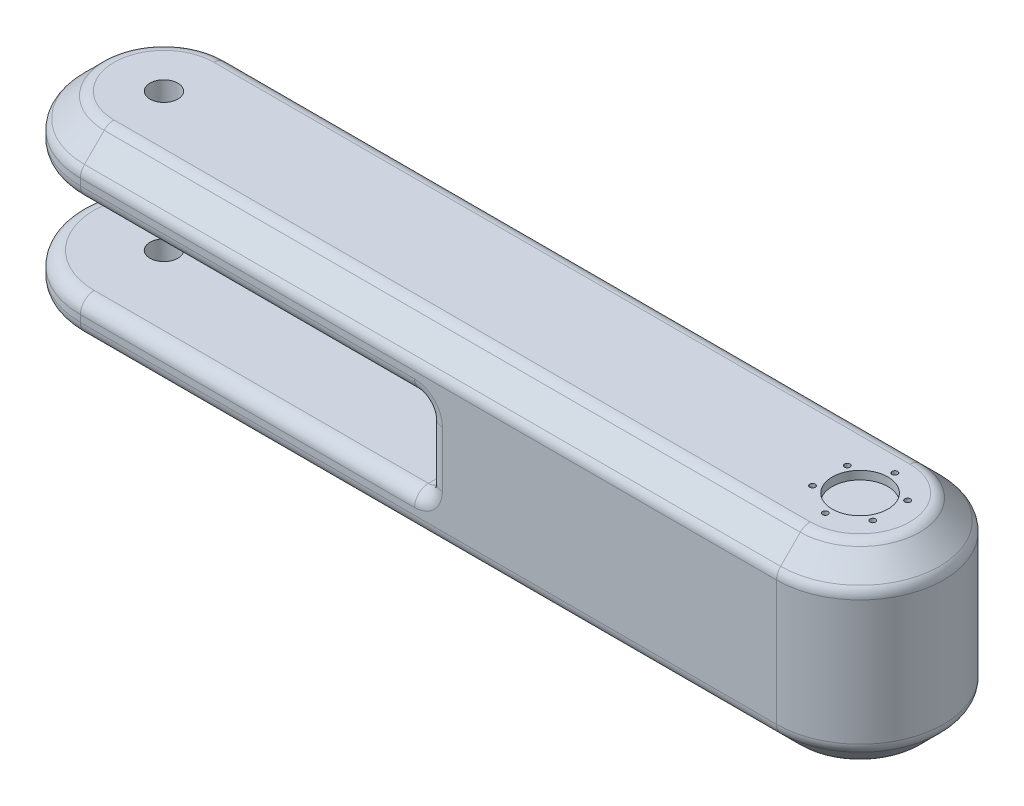
SolidWorks part; units mm, degrees
ref_plane "Front Plane" through (0, 0, 0) normal (0, 0, 1) x (1, 0, 0)
ref_plane "Top Plane" through (0, 0, 0) normal (0, 1, 0) x (1, 0, 0)
ref_plane "Right Plane" through (0, 0, 0) normal (1, 0, 0) x (0, 0, -1)
sketch "Sketch1" plane through (0, 0, 0) normal (0, 1, 0) x (1, 0, 0)
  line L0 (-125, 0) -> (125, 0) construction
  line L1 (-125, 30) -> (125, 30)
  line L2 (-125, -30) -> (125, -30)
  arc A0 (-125, 30) -> (-125, -30) centre (-125, 0) ccw
  arc A1 (125, -30) -> (125, 30) centre (125, 0) ccw
  point P2 (0, 0)
  dimension "D1" = 30
  dimension "D2" = 250
extrude "Boss-Extrude1" add sketch "Sketch1" along normal mid plane 69
sketch "Sketch2" plane through (0, 34.5, 0) normal (0, 1, 0) x (1, 0, 0)
  circle A0 centre (125, 0) radius 10
  dimension "D1" = 20
extrude "Cut-Extrude1" cut sketch "Sketch2" against normal blind 3
sketch "Sketch3" plane through (0, -34.5, 0) normal (0, -1, 0) x (1, 0, 0)
  line L2 (-125, -30) -> (125, -30)
  line L3 (125, 30) -> (-125, 30)
  line L4 (-125, -30) -> (125, -30)
  line L5 (125, 30) -> (-125, 30)
  arc A2 (-125, 30) -> (-125, -30) centre (-125, 0) ccw
  arc A3 (125, -30) -> (125, 30) centre (125, 0) ccw
  arc A4 (-125, 30) -> (-125, -30) centre (-125, 0) ccw
  arc A5 (125, -30) -> (125, 30) centre (125, 0) ccw
  dimension "D1" = 0
sketch "Sketch4" plane through (0, -34.5, 0) normal (0, -1, 0) x (1, 0, 0)
  circle A0 centre (125, 0) radius 10
  dimension "D1" = 20
extrude "Cut-Extrude2" cut sketch "Sketch4" against normal blind 3
chamfer "Chamfer1" distance 10 angle 45 8 edges at (0, -34.5, -30) (-155, -34.5, 0) (155, -34.5, 0) (0, -34.5, 30) (0, 34.5, -30) (-155, 34.5, 0) (155, 34.5, 0) (0, 34.5, 30)
fillet "Fillet1" radius 5 16 edges at (155, 24.5, 0) (0, 24.5, -30) (-155, 24.5, 0) (-155, -24.5, 0) (0, -24.5, -30) (155, -24.5, 0) (145, -34.5, 0) (0, -34.5, -20) (-145, -34.5, 0) (-145, 34.5, 0) (0, 34.5, -20) (145, 34.5, 0) (0, 24.5, 30) (0, -24.5, 30) (0, -34.5, 20) (0, 34.5, 20)
sketch "Sketch5" plane through (0, 0, -30) normal (0, 0, -1) x (-1, 0, 0)
  line L0 (0, 15) -> (0, -15)
  line L1 (0, -15) -> (155, -15)
  line L2 (155, -22.4289) -> (155, 22.4289) construction
  line L3 (155, -15) -> (155, 15)
  line L4 (155, 15) -> (0, 15)
  line L5 (0, 15) -> (0.7439, 15.372)
  point P3 (0, 0)
  line M3 (125, -22.4289) -> (125, 22.4289)
  dimension "D1" = 30
extrude "Cut-Extrude3" cut sketch "Sketch5" against normal through all contours L4 L0 L1 M3 | L3 L4 L1 M3
fillet "Fillet2" radius 5 10 edges at (0, 0, 30) (-62.5, 15, 30) (-62.5, -15, 30) (-155, 15, 0) (-155, -15, 0) (-62.5, 15, -30) (-62.5, -15, -30) (0, 0, -30) (0, -15, 0) (0, 15, 0)
sketch "Sketch6" plane through (0, -34.5, 0) normal (0, -1, 0) x (1, 0, 0)
  circle A0 centre (-125, 0) radius 5
  dimension "D1" = 10
extrude "Cut-Extrude4" cut sketch "Sketch6" against normal through all
sketch "Sketch7" plane through (0, 34.5, 0) normal (0, 1, 0) x (1, 0, 0)
  line L0 (125, 0) -> (125, 12.5) construction
  circle A0 centre (125, 0) radius 12.5 construction
  dimension "D1" = 25
hole_wizard "Ø2.0mm Dowel Hole1" positions "3DSketch1" profile "Sketch8" hole size "Ø2.0" standard "ANSI Metric"
sketch3d "3DSketch1"
  point P0 (125, 34.5, -12.5)
sketch "Sketch8" plane through (125, 34.5, -12.5) normal (1, 0, 0) x (0, 0, 1)
  line L0 (0, 0) -> (0, 5.6009)
  line L1 (0, 5.6009) -> (1, 5)
  line L2 (1, 5) -> (1, 0)
  line L5 (1, 0) -> (0, 0)
  line L10 (0, 5.6009) -> (-1, 5) construction
  line L11 (0, -6.35) -> (0, 107.95) construction
  dimension "Hole Dia." = 2
  dimension "Hole Depth" = 5
  dimension "Drill Angle" = 118
pattern_circular "CirPattern1" count 6 over 360 about axis through (125, 0, 0) along (0, 1, 0) of "Ø2.0mm Dowel Hole1"
sketch "Sketch9" plane through (0, -34.5, 0) normal (0, -1, 0) x (1, 0, 0)
  line L0 (125, 0) -> (125, 12.5) construction
  circle A0 centre (125, 0) radius 12.5 construction
  dimension "D1" = 25
hole_wizard "Ø2.0mm Dowel Hole2" positions "3DSketch2" profile "Sketch10" hole size "Ø2.0" standard "ANSI Metric"
sketch3d "3DSketch2"
  point P0 (125, -34.5, 12.5)
sketch "Sketch10" plane through (125, -34.5, 12.5) normal (1, 0, 0) x (0, 0, -1)
  line L0 (0, 0) -> (0, 5.6009)
  line L1 (0, 5.6009) -> (1, 5)
  line L2 (1, 5) -> (1, 0)
  line L5 (1, 0) -> (0, 0)
  line L10 (0, 5.6009) -> (-1, 5) construction
  line L11 (0, -6.35) -> (0, 107.95) construction
  dimension "Hole Dia." = 2
  dimension "Hole Depth" = 5
  dimension "Drill Angle" = 118
pattern_circular "CirPattern2" count 6 over 360 about axis through (125, 0, 0) along (0, 1, 0) of "Ø2.0mm Dowel Hole2"
ref_plane "Gravity" through (0, 0, 0) normal (0.7071, 0, 0.7071) x (0.7071, 0, -0.7071)
